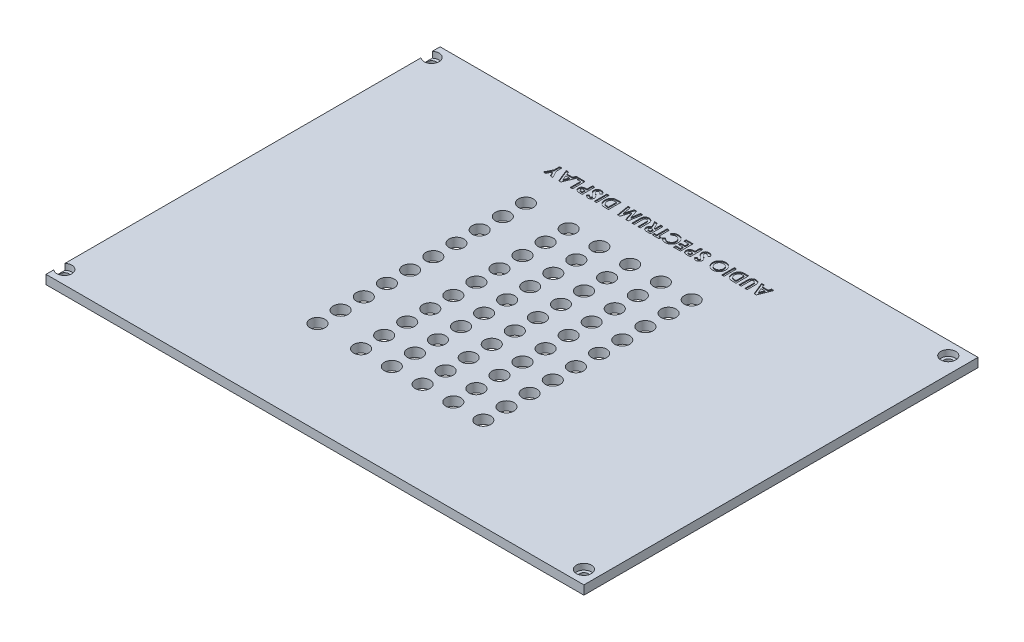
SolidWorks part; units mm, degrees
ref_plane "Front Plane" through (0, 0, 0) normal (0, 0, 1) x (1, 0, 0)
ref_plane "Top Plane" through (0, 0, 0) normal (0, 1, 0) x (1, 0, 0)
ref_plane "Right Plane" through (0, 0, 0) normal (1, 0, 0) x (0, 0, -1)
sketch "Sketch1" plane through (0, 0, 0) normal (0, 1, 0) x (1, 0, 0)
  line L1 (-90.08, 66) -> (90.08, 66)
  line L2 (-90.08, 66) -> (-90.08, -66)
  line L3 (-90.08, -66) -> (90.08, -66)
  line L4 (90.08, 66) -> (90.08, -66)
  line L5 (-90.08, 66) -> (90.08, -66) construction
  line L6 (-90.08, -66) -> (90.08, 66) construction
  point P0 (0, 0)
  dimension "D1" = 180.16
  dimension "D2" = 132
extrude "Boss-Extrude1" add sketch "Sketch1" along normal blind 3
sketch "Sketch2" plane through (0, 3, 0) normal (0, 1, 0) x (1, 0, 0)
  line L0 (-90.08, 66) -> (-90.08, -66) construction
  line L1 (90.08, 66) -> (-90.08, 66) construction
  line L2 (90.08, -66) -> (90.08, 66) construction
  line L3 (-90.08, -66) -> (90.08, -66) construction
  circle A0 centre (-88.42, 61.5) radius 2.5
  circle A2 centre (84.6218, 61.5) radius 2.5
  circle A3 centre (85.58, -61.5) radius 2.5
  circle A4 centre (-88.42, -61.5) radius 2.5
  point P0 (-88.42, 61.5)
  point P1 (84.6218, 61.5)
  point P2 (85.58, -61.5)
  point P3 (-88.42, -61.5)
  point P4 (-88.42, 61.5)
  dimension "D1" = 1.66
  dimension "D2" = 4.5
  dimension "D3" = 4.5
  dimension "D4" = 4.5
  dimension "D5" = 4.5
  dimension "D6" = 1.66
  dimension "D7" = 4.5
extrude "Cut-Extrude1" cut sketch "Sketch2" against normal blind 2
sketch "Sketch3" plane through (0, 1, 0) normal (0, 1, 0) x (1, 0, 0)
  circle A0 centre (-88.42, 61.5) radius 1.5
  circle A1 centre (84.6218, 61.5) radius 1.5
  circle A2 centre (85.58, -61.5) radius 1.5
  circle A3 centre (-88.42, -61.5) radius 1.5
extrude "Cut-Extrude2" cut sketch "Sketch3" against normal blind 2
sketch "Sketch4" plane through (0, 3, 0) normal (0, 1, 0) x (1, 0, 0)
  circle A10 centre (-15.7297, 34.6992) radius 2.5
  circle A11 centre (-15.7297, 26.9751) radius 2.5
  circle A12 centre (-15.7297, 19.251) radius 2.5
  circle A13 centre (-15.7297, 11.5269) radius 2.5
  circle A14 centre (-15.7297, 3.8027) radius 2.5
  circle A15 centre (-15.7297, -3.9214) radius 2.5
  circle A16 centre (-15.7297, -11.6455) radius 2.5
  circle A17 centre (-15.7297, -19.3696) radius 2.5
  circle A18 centre (-15.7297, -27.0937) radius 2.5
  circle A19 centre (-15.7297, -34.8179) radius 2.5
  circle A20 centre (-5.4316, 34.6992) radius 2.5
  circle A21 centre (-5.4316, 26.9751) radius 2.5
  circle A22 centre (-5.4316, 19.251) radius 2.5
  circle A23 centre (-5.4316, 11.5269) radius 2.5
  circle A24 centre (-5.4316, 3.8027) radius 2.5
  circle A25 centre (-5.4316, -3.9214) radius 2.5
  circle A26 centre (-5.4316, -11.6455) radius 2.5
  circle A27 centre (-5.4316, -19.3696) radius 2.5
  circle A28 centre (-5.4316, -27.0937) radius 2.5
  circle A29 centre (-5.4316, -34.8179) radius 2.5
  circle A30 centre (4.8664, 34.6992) radius 2.5
  circle A31 centre (4.8664, 26.9751) radius 2.5
  circle A32 centre (4.8664, 19.251) radius 2.5
  circle A33 centre (4.8664, 11.5269) radius 2.5
  circle A34 centre (4.8664, 3.8027) radius 2.5
  circle A35 centre (4.8664, -3.9214) radius 2.5
  circle A36 centre (4.8664, -11.6455) radius 2.5
  circle A37 centre (4.8664, -19.3696) radius 2.5
  circle A38 centre (4.8664, -27.0937) radius 2.5
  circle A39 centre (4.8664, -34.8179) radius 2.5
  circle A40 centre (15.1645, 34.6992) radius 2.5
  circle A41 centre (15.1645, 26.9751) radius 2.5
  circle A42 centre (15.1645, 19.251) radius 2.5
  circle A43 centre (15.1645, 11.5269) radius 2.5
  circle A44 centre (15.1645, 3.8027) radius 2.5
  circle A45 centre (15.1645, -3.9214) radius 2.5
  circle A46 centre (15.1645, -11.6455) radius 2.5
  circle A47 centre (15.1645, -19.3696) radius 2.5
  circle A48 centre (15.1645, -27.0937) radius 2.5
  circle A49 centre (15.1645, -34.8179) radius 2.5
extrude "Cut-Extrude3" cut sketch "Sketch4" against normal blind 12
sketch "Sketch6" plane through (0, 3, 0) normal (0, 1, 0) x (1, 0, 0)
  circle A0 centre (25.4722, 34.7208) radius 2.5
  circle A1 centre (25.4722, 26.9653) radius 2.5
  circle A2 centre (25.4722, 19.2097) radius 2.5
  circle A3 centre (25.4722, 11.4541) radius 2.5
  circle A4 centre (25.4722, 3.6986) radius 2.5
  circle A5 centre (25.4722, -4.057) radius 2.5
  circle A6 centre (25.4722, -11.8125) radius 2.5
  circle A7 centre (25.4722, -19.5681) radius 2.5
  circle A8 centre (25.4722, -27.3236) radius 2.5
  circle A9 centre (25.4722, -35.0792) radius 2.5
  dimension "D1" = 10
extrude "Cut-Extrude4" cut sketch "Sketch6" against normal blind 12
sketch "Sketch11" plane through (0, 3, 0) normal (0, 1, 0) x (1, 0, 0)
  line L0 (25.4722, -35.0792) -> (-15.7297, -34.8179) construction
  line L1 (-15.7297, -34.8179) -> (-38.0501, -34.8179) construction
  circle A0 centre (-30.3429, -34.8179) radius 2.5
  circle A1 centre (-30.3429, -27.0579) radius 2.5
  circle A2 centre (-30.3429, -19.2979) radius 2.5
  circle A3 centre (-30.3429, -11.5379) radius 2.5
  circle A4 centre (-30.3429, -3.7779) radius 2.5
  circle A5 centre (-30.3429, 3.9821) radius 2.5
  circle A6 centre (-30.3429, 11.7421) radius 2.5
  circle A7 centre (-30.3429, 19.5021) radius 2.5
  circle A8 centre (-30.3429, 27.2621) radius 2.5
  circle A9 centre (-30.3429, 35.0221) radius 2.5
  dimension "D1" = 10
extrude "Cut-Extrude8" cut sketch "Sketch11" against normal blind 12
sketch "Sketch12" plane through (0, 3, 0) normal (0, 1, 0) x (1, 0, 0)
  line L0 (39.5499, 51.2096) -> (-39.7364, 51.2096) construction
  text T0 "AUDIO SPECTRUM DISPLAY" font "Century Gothic" height in points 16
extrude "Cut-Extrude9" cut sketch "Sketch12" against normal blind 0.3
